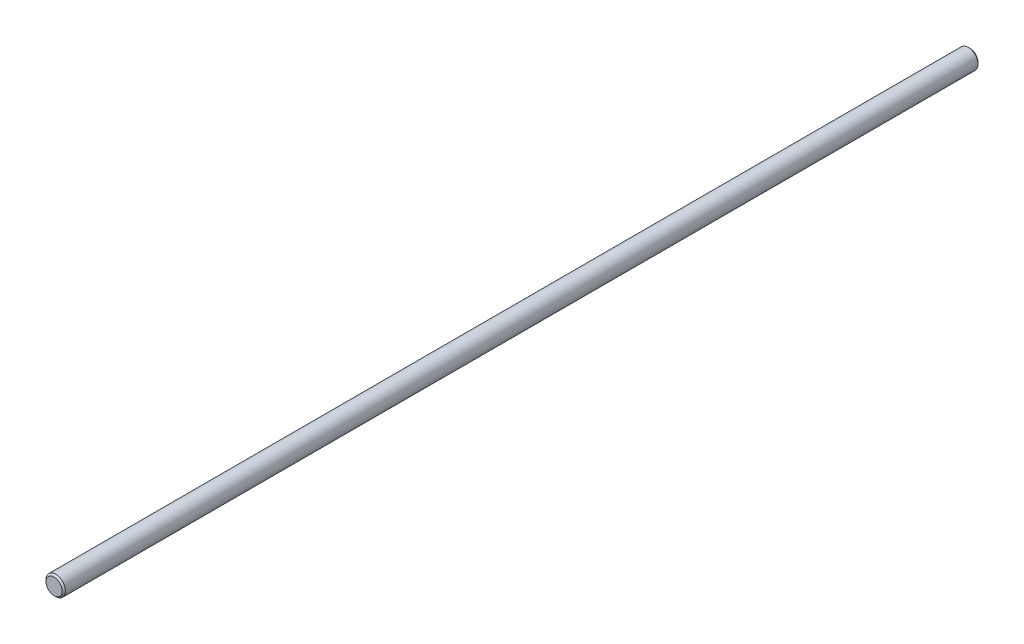
SolidWorks part; units mm, degrees
ref_plane "Front Plane" through (0, 0, 0) normal (0, 0, 1) x (1, 0, 0)
ref_plane "Top Plane" through (0, 0, 0) normal (0, 1, 0) x (1, 0, 0)
ref_plane "Right Plane" through (0, 0, 0) normal (1, 0, 0) x (0, 0, -1)
sketch "Sketch2" plane through (0, 0, 0) normal (0, 0, 1) x (1, 0, 0)
  circle A0 centre (0, 0) radius 3
  dimension "D1" = 6
extrude "Boss-Extrude1" add sketch "Sketch2" along normal mid plane 282.5
chamfer "Chamfer1" distance 0.5 angle 45 2 edges at (3, 0, -141.25) (3, 0, 141.25)
